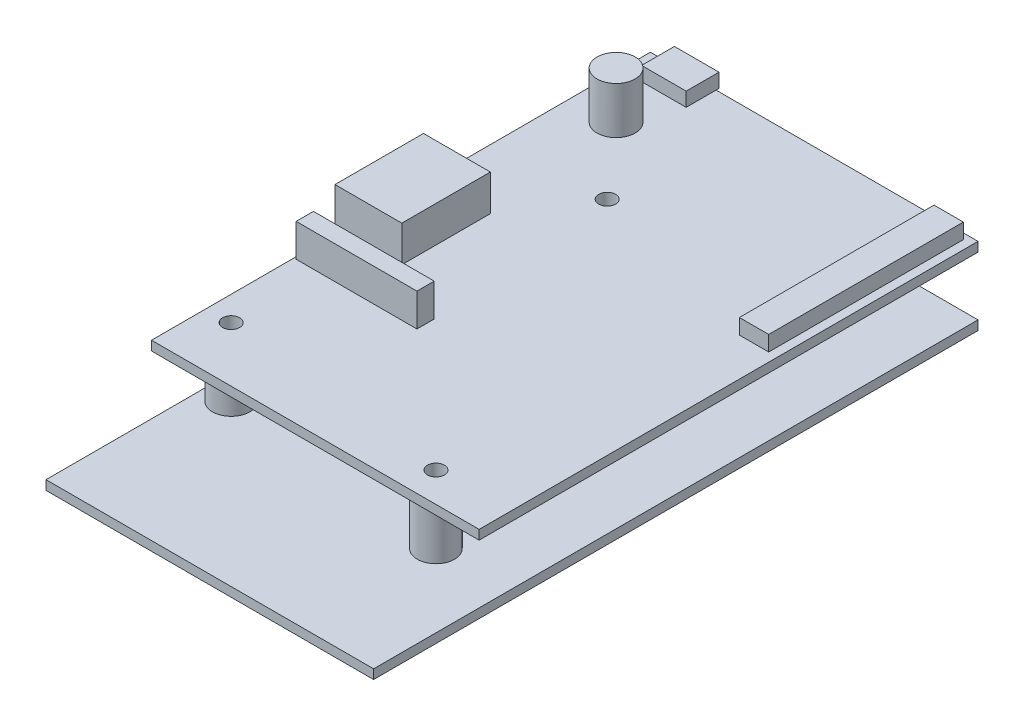
SolidWorks part; units mm, degrees
ref_plane "Front Plane" through (0, 0, 0) normal (0, 0, 1) x (1, 0, 0)
ref_plane "Top Plane" through (0, 0, 0) normal (0, 1, 0) x (1, 0, 0)
ref_plane "Right Plane" through (0, 0, 0) normal (1, 0, 0) x (0, 0, -1)
sketch "Sketch2" plane through (0, 0, 0) normal (0, 1, 0) x (1, 0, 0)
  line L1 (27.94, 42.545) -> (-27.94, 42.545)
  line L2 (27.94, 42.545) -> (27.94, -42.545)
  line L3 (27.94, -42.545) -> (-27.94, -42.545)
  line L4 (-27.94, 42.545) -> (-27.94, -42.545)
  line L5 (27.94, 42.545) -> (-27.94, -42.545) construction
  line L6 (27.94, -42.545) -> (-27.94, 42.545) construction
  point P0 (0, 0)
  dimension "D1" = 55.88
  dimension "D2" = 85.09
extrude "Fiberglass PCB" add sketch "Sketch2" along normal blind 1.6
sketch "Sketch3" plane through (0, 1.6, 0) normal (0, 1, 0) x (1, 0, 0)
  line L0 (-27.94, 42.545) -> (-27.94, -42.545) construction
  line L1 (-24.34, 43.045) -> (-16.74, 43.045)
  line L2 (-24.34, 43.045) -> (-24.34, 37.445)
  line L3 (-24.34, 37.445) -> (-16.74, 37.445)
  line L4 (-16.74, 43.045) -> (-16.74, 37.445)
  line L5 (27.94, 42.545) -> (-27.94, 42.545) construction
  dimension "D1" = 7.6
  dimension "D2" = 5.6
  dimension "D3" = 3.6
  dimension "D4" = 0.5
extrude "USB Micro-B Power" add sketch "Sketch3" along normal blind 2.4
sketch "Sketch4" plane through (0, 1.6, 0) normal (0, 1, 0) x (1, 0, 0)
  line L0 (27.94, -42.545) -> (27.94, 42.545) construction
  line L1 (21.44, 41.545) -> (26.44, 41.545)
  line L2 (21.44, 41.545) -> (21.44, 8.345)
  line L3 (21.44, 8.345) -> (26.44, 8.345)
  line L4 (26.44, 41.545) -> (26.44, 8.345)
  line L5 (27.94, 42.545) -> (-16.74, 42.545) construction
  dimension "D1" = 5
  dimension "D2" = 1.5
  dimension "D3" = 33.2
  dimension "D4" = 1
extrude "Boss-Extrude3" add sketch "Sketch4" along normal blind 2.6
sketch "Sketch5" plane through (0, 1.6, 0) normal (0, 1, 0) x (1, 0, 0)
  line L0 (-27.94, 42.545) -> (-27.94, -42.545) construction
  line L1 (-29.14, 5.045) -> (-17.74, 5.045)
  line L2 (-29.14, 5.045) -> (-29.14, -10.055)
  line L3 (-29.14, -10.055) -> (-17.74, -10.055)
  line L4 (-17.74, 5.045) -> (-17.74, -10.055)
  line L5 (-24.34, 42.545) -> (-27.94, 42.545) construction
  dimension "D1" = 15.1
  dimension "D2" = 11.4
  dimension "D3" = 1.2
  dimension "D4" = 37.5
extrude "Boss-Extrude4" add sketch "Sketch5" along normal blind 6.15
sketch "Sketch6" plane through (0, 1.6, 0) normal (0, 1, 0) x (1, 0, 0)
  line L0 (-27.94, 42.545) -> (-27.94, 5.045) construction
  line L1 (-10.29, 31.995) -> (10.31, 31.995)
  line L2 (-10.29, 31.995) -> (-10.29, 29.045)
  line L3 (-10.29, 29.045) -> (10.31, 29.045)
  line L4 (10.31, 31.995) -> (10.31, 29.045)
  line L5 (27.94, 42.545) -> (-16.74, 42.545) construction
  line L6 (-27.56, -15.305) -> (-6.96, -15.305)
  line L7 (-27.56, -15.305) -> (-27.56, -18.255)
  line L8 (-27.56, -18.255) -> (-6.96, -18.255)
  line L9 (-6.96, -15.305) -> (-6.96, -18.255)
  line L10 (-27.94, -10.055) -> (-17.74, -10.055) construction
  line L11 (27.94, -42.545) -> (27.94, 42.545) construction
  dimension "D1" = 2.95
  dimension "D2" = 20.6
  dimension "D3" = 17.65
  dimension "D4" = 13.5
  dimension "D5" = 20.6
  dimension "D6" = 2.95
  dimension "D7" = 5.25
  dimension "D8" = 34.9
extrude "Boss-Extrude5" add sketch "Sketch6" along normal blind 5.6 contours L9 L6 L7 L8
sketch "Sketch8" plane through (0, 1.6, 0) normal (0, 1, 0) x (1, 0, 0)
  line L1 (-23.79, 34.459) -> (-23.79, 23.8042) construction
  line L2 (-27.94, 42.545) -> (-27.94, 5.045) construction
  line L3 (-25.2461, 32.545) -> (-15.6058, 32.545) construction
  line L4 (-24.34, 42.545) -> (-27.94, 42.545) construction
  circle A0 centre (-20.54, 29.295) radius 3.25
  dimension "D1" = 6.5
  dimension "D2" = 4.15
  dimension "D3" = 10
extrude "Boss-Extrude6" add sketch "Sketch8" along normal blind 8
sketch "Sketch9" plane through (0, 0, 0) normal (0, -1, 0) x (1, 0, 0)
  line L0 (-27.94, -42.545) -> (-27.94, 42.545) construction
  line L1 (-12.94, -24.545) -> (15.46, -24.545)
  line L2 (-12.94, -24.545) -> (-12.94, -41.345)
  line L3 (-12.94, -41.345) -> (15.46, -41.345)
  line L4 (15.46, -24.545) -> (15.46, -41.345)
  line L5 (27.94, -42.545) -> (-27.94, -42.545) construction
  dimension "D1" = 28.4
  dimension "D2" = 16.8
  dimension "D3" = 43.4
  dimension "D4" = 18
extrude "Boss-Extrude7" add sketch "Sketch9" along normal blind 3.9
sketch "Sketch10" plane through (0, 0, -41.345) normal (0, 0, -1) x (-1, 0, 0)
  line L1 (-14.097, -1.05) -> (9.903, -1.05)
  line L2 (-14.097, -1.05) -> (-14.097, -3.15)
  line L3 (-14.097, -3.15) -> (9.903, -3.15)
  line L4 (9.903, -1.05) -> (9.903, -3.15)
  line L5 (12.94, -3.9) -> (-15.46, -3.9) construction
  line L6 (-27.94, 1.6) -> (-27.94, 0) construction
  dimension "D1" = 2.1
  dimension "D2" = 24
  dimension "D3" = 13.843
  dimension "D4" = 0.75
extrude "Boss-Extrude8" add sketch "Sketch10" along normal blind 2.286
sketch "Sketch11" plane through (0, 1.6, 0) normal (0, 1, 0) x (1, 0, 0)
  line L0 (14.097, 43.631) -> (-9.903, 43.631) construction
  line L1 (-9.903, 43.631) -> (-9.903, 41.345) construction
  line L4 (-27.94, 42.545) -> (-27.94, 5.045) construction
  line L5 (27.94, 42.545) -> (-16.74, 42.545) construction
  line L6 (-27.94, -42.545) -> (27.94, -42.545) construction
  line L7 (27.94, -42.545) -> (27.94, 42.545) construction
  circle A0 centre (15.494, -37.465) radius 1.45
  circle A1 centre (-9.906, 17.145) radius 1.45
  dimension "D1" = 2.9
  dimension "D2" = 2.9
  dimension "D3" = 18.034
  dimension "D4" = 25.4
  dimension "D5" = 5.08
  dimension "D6" = 12.446
  dimension "D7" = 54.61
  dimension "D8" = 25.4
  dimension "D9" = 26.486
  dimension "D10" = 0.003
extrude "Cut-Extrude1" cut sketch "Sketch11" against normal through all
sketch "Sketch12" plane through (0, 0, 0) normal (0, -1, 0) x (1, 0, 0)
  circle A0 centre (-9.906, -17.145) radius 3.175
  circle A1 centre (15.494, 37.465) radius 3.175
  dimension "D1" = 6.35
  dimension "D2" = 6.35
extrude "Boss-Extrude9" add sketch "Sketch12" along normal blind 10
sketch "Sketch13" plane through (0, -10, 0) normal (0, -1, 0) x (1, 0, 0)
  line L0 (-27.94, -42.545) -> (-27.94, 42.545) construction
  line L1 (-27.94, -42.545) -> (27.94, -42.545)
  line L2 (-27.94, -42.545) -> (-27.94, 60.545)
  line L3 (-27.94, 60.545) -> (27.94, 60.545)
  line L4 (27.94, -42.545) -> (27.94, 60.545)
  line L5 (27.94, 42.545) -> (27.94, -42.545) construction
  line L6 (-27.94, 42.545) -> (27.94, 42.545) construction
  line L7 (27.94, -42.545) -> (-27.94, -42.545) construction
  dimension "D1" = 18
extrude "Boss-Extrude10" add sketch "Sketch13" along normal blind 1.5875
sketch "Sketch14" plane through (0, 1.6, 0) normal (0, 1, 0) x (1, 0, 0)
  circle A0 centre (-9.906, 17.145) radius 1.45
  circle A1 centre (15.494, -37.465) radius 1.45
extrude "Cut-Extrude2" cut sketch "Sketch14" against normal through all
sketch "Sketch15" plane through (0, -3.9, 0) normal (0, -1, 0) x (-1, 0, 0)
  line L0 (-14.097, 41.345) -> (9.903, 41.345) construction
  line L1 (8.7335, 41.345) -> (-12.412, 41.345)
  line L2 (8.7335, 41.345) -> (8.7335, 27.883)
  line L3 (8.7335, 27.883) -> (-10.1669, 27.883)
  line L4 (-12.412, 41.345) -> (-12.412, 30.1281)
  line L5 (-15.46, 41.345) -> (-15.46, 24.545) construction
  line L7 (-10.1669, 27.883) -> (-12.412, 30.1281)
  point P1 (-12.412, 27.883)
  dimension "D1" = 21.1455
  dimension "D2" = 3.048
  dimension "D3" = 13.462
  dimension "D4" = 3.175
  dimension "D5" = 45
extrude "Cut-Extrude3" cut sketch "Sketch15" against normal up to surface (0.75 mm away) up to face at (2.097, -3.15, -42.488)
sketch "Sketch16" plane through (0, -3.15, 0) normal (0, -1, 0) x (1, 0, 0)
  line L0 (10.1669, -27.883) -> (-8.7335, -27.883) construction
  line L1 (-5.2156, -28.899) -> (8.8179, -28.899)
  line L2 (-5.2156, -28.899) -> (-5.2156, -46.044)
  line L3 (-5.2156, -46.044) -> (8.8179, -46.044)
  line L4 (8.8179, -28.899) -> (8.8179, -46.044)
  line L5 (-8.7335, -27.883) -> (-8.7335, -41.345) construction
  dimension "D1" = 14.0335
  dimension "D2" = 17.145
  dimension "D3" = 1.016
  dimension "D4" = 3.5179
extrude "Boss-Extrude11" add sketch "Sketch16" along normal blind 1.9685
sketch "Sketch18" plane through (0, 1.6, 0) normal (0, 1, 0) x (1, 0, 0)
  line L0 (27.94, 42.545) -> (-16.74, 42.545) construction
  line L2 (-27.94, -10.055) -> (-27.94, -42.545) construction
  circle A0 centre (-23.749, -33.1597) radius 3.175
  dimension "D1" = 75.7047
  dimension "D3" = 6.35
  dimension "D2" = 4.191
extrude "Boss-Extrude13" add sketch "Sketch18" against normal through all contours A0
sketch "Sketch19" plane through (0, 1.6, 0) normal (0, 1, 0) x (1, 0, 0)
  circle A0 centre (-23.749, -33.1597) radius 1.45
  circle A1 centre (-23.749, -33.1597) radius 3.175 construction
  circle A2 centre (15.494, -37.465) radius 1.45 construction
extrude "Cut-Extrude5" cut sketch "Sketch19" against normal through all
